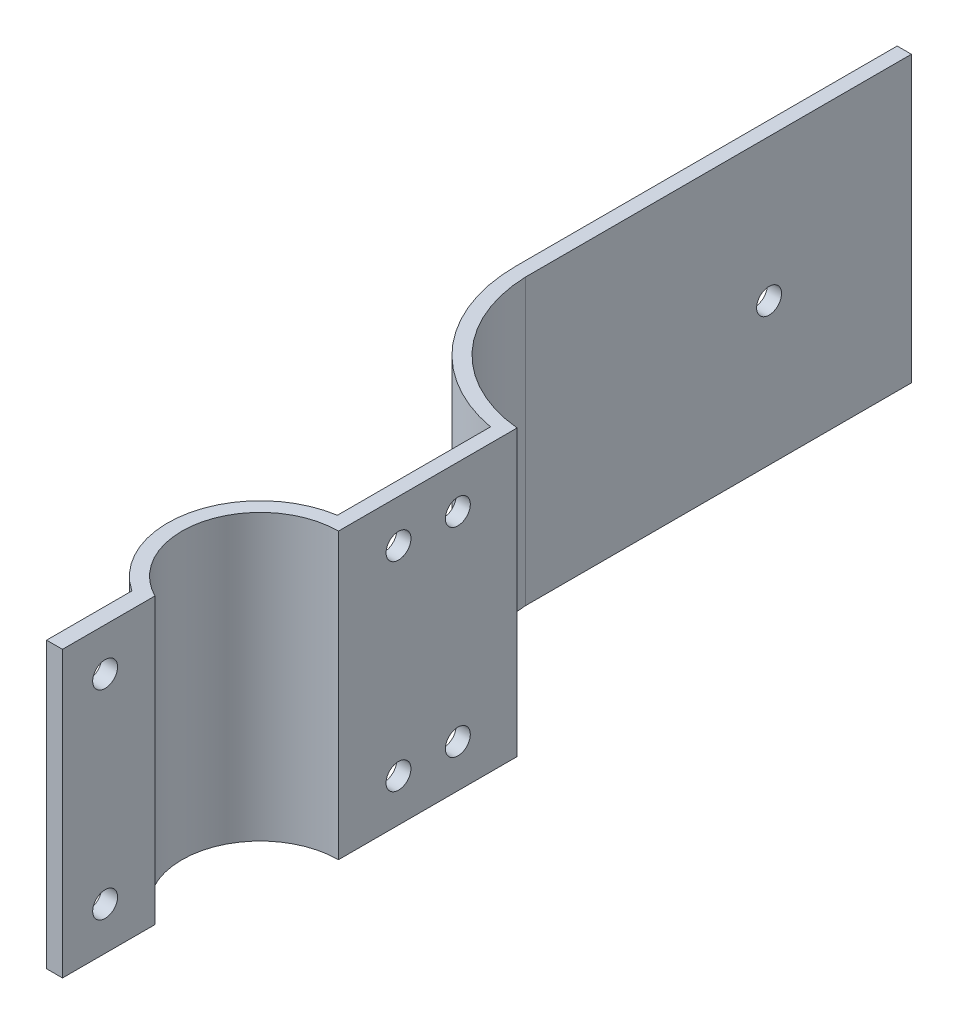
SolidWorks part; units mm, degrees
ref_plane "Front Plane" through (0, 0, 0) normal (0, 0, 1) x (1, 0, 0)
ref_plane "Top Plane" through (0, 0, 0) normal (0, 1, 0) x (1, 0, 0)
ref_plane "Right Plane" through (0, 0, 0) normal (1, 0, 0) x (0, 0, -1)
sketch "Sketch1" plane through (0, 0, 0) normal (0, 1, 0) x (1, 0, 0)
  line L0 (0, 91.2362) -> (0, 0) construction
  line L1 (0, 11) -> (0, 36.0988)
  line L2 (-2, 12.8452) -> (-2, 34.3634)
  line L3 (-19.7762, 55.701) -> (-19.7762, 109.2874)
  line L4 (-5, 25.8533) -> (-2, 25.8533) construction
  line L5 (-15, 136.2362) -> (15, 136.2362) construction
  line L6 (-15, 136.2362) -> (-15, 46.2362) construction
  line L7 (-15, 46.2362) -> (15, 46.2362) construction
  line L8 (15, 136.2362) -> (15, 46.2362) construction
  line L9 (-15, 136.2362) -> (15, 46.2362) construction
  line L10 (-15, 46.2362) -> (15, 136.2362) construction
  line L11 (-5, 15.3533) -> (-2, 15.3533) construction
  line L12 (-5, 15.3533) -> (-5, 20.8533) construction
  line L13 (-5, 20.8533) -> (-2, 20.8533) construction
  line L14 (-2, 15.3533) -> (-2, 20.8533) construction
  line L15 (-5, 15.3533) -> (-2, 20.8533) construction
  line L16 (-5, 20.8533) -> (-2, 15.3533) construction
  line L17 (-5, 25.8533) -> (-5, 31.3533) construction
  line L18 (-5, 31.3533) -> (-2, 31.3533) construction
  line L19 (-2, 25.8533) -> (-2, 31.3533) construction
  line L20 (-5, 25.8533) -> (-2, 31.3533) construction
  line L21 (-5, 31.3533) -> (-2, 25.8533) construction
  line L22 (-5, -9.798) -> (-5, -22.784)
  line L23 (-10.234, -19.9216) -> (-7.234, -19.9216) construction
  line L24 (-10.234, -19.9216) -> (-10.234, -14.4216) construction
  line L25 (-10.234, -14.4216) -> (-7.234, -14.4216) construction
  line L26 (-7.234, -19.9216) -> (-7.234, -14.4216) construction
  line L27 (-10.234, -19.9216) -> (-7.234, -14.4216) construction
  line L28 (-10.234, -14.4216) -> (-7.234, -19.9216) construction
  line L29 (-5, -22.784) -> (-7.234, -22.784)
  line L30 (-7.234, -22.784) -> (-7.234, -10.8013)
  line L31 (-17.7762, 109.2874) -> (-17.7762, 55.0391)
  line L32 (-19.7762, 109.2874) -> (-17.7762, 109.2874)
  line L33 (0, 91.2362) -> (-30.4033, 91.2362) construction
  arc A0 (0, 11) -> (-5, -9.798) centre (0, 0) ccw
  arc A1 (-2, 34.3634) -> (-19.7762, 55.701) centre (1.9182, 55.701) cw
  arc A2 (-2, 12.8452) -> (-7.234, -10.8013) centre (0, 0) ccw
  circle A3 centre (0, 0) radius 11 construction
  circle A4 centre (0, 0) radius 13 construction
  arc A5 (0, 36.0988) -> (-17.7762, 55.0391) centre (1.9144, 55.7075) cw
  point P4 (0, 23.5494)
  point P5 (-8.734, -17.1716)
  point P10 (0, 91.2362)
  point P17 (-3.5, 28.6033)
  point P20 (-3.5, 18.1033)
  point P33 (-17.7762, 117.3644)
  point P43 (-10.0392, -19.1294)
  point P44 (-8.734, -17.1716)
  point P45 (0, 91.2362)
  dimension "D1" = 22
  dimension "D2" = 30
  dimension "D14" = 2
  dimension "D3" = 90
  dimension "D4" = 5.5
  dimension "D5" = 3
  dimension "D6" = 5.5
  dimension "D7" = 3
  dimension "D8" = 2
  dimension "D9" = 5
  dimension "D11" = 5.5
  dimension "D12" = 3
  dimension "D13" = 10
  dimension "D15" = 2
  dimension "D10" = 2
extrude "Boss-Extrude1" add sketch "Sketch1" along normal blind 40
sketch "Sketch3" plane through (-2, 0, 0) normal (-1, 0, 0) x (0, 0, 1)
  line L0 (-109.2874, 20) -> (22.784, 20) construction
  line L1 (-109.2874, 40) -> (-109.2874, 0) construction
  line L2 (22.784, 40) -> (22.784, 0) construction
  line L3 (-17.6846, 6) -> (-12.8452, 6) construction
  line L4 (-34.3634, 40) -> (-12.8452, 40) construction
  line L5 (16.7926, 40) -> (16.7926, 0) construction
  line L6 (10.8013, 40) -> (22.784, 40) construction
  line L7 (10.8013, 0) -> (22.784, 0) construction
  line L8 (-29.524, 34) -> (-34.3634, 34) construction
  line L10 (-34.3634, 40) -> (-34.3634, 0) construction
  line L11 (-26.024, 34) -> (-21.1846, 34) construction
  line L13 (-26.024, 6) -> (-21.1846, 6) construction
  line L14 (-29.524, 6) -> (-34.3634, 6) construction
  line L15 (-17.6846, 34) -> (-12.8452, 34) construction
  line L16 (-12.8452, 40) -> (-12.8452, 0) construction
  circle A0 centre (-27.774, 34) radius 1.75
  circle A1 centre (-19.4346, 34) radius 1.75
  circle A2 centre (16.7926, 34) radius 1.75
  circle A3 centre (-89.2874, 20) radius 1.75
  circle A4 centre (16.7926, 6) radius 1.75
  circle A5 centre (-19.4346, 6) radius 1.75
  circle A6 centre (-27.774, 6) radius 1.75
  point P28 (16.7926, 34)
  point P29 (0, 0)
  point P34 (-92.1249, 20)
  dimension "D1" = 3.5
  dimension "D2" = 6
  dimension "D3" = 20
extrude "Cut-Extrude1" cut sketch "Sketch3" against normal through all both and the other way through all
surface "Surface-Flatten1"
sketch "Sketch4" plane through (-17.7762, 0, -84.5383) normal (1, 0, 0) x (0, 0, -1)
  spline S0 degree 1 poles (-29.4994, 40.0006) (-29.4996, -0.0002) knots 0 0 1 1
  spline S1 degree 1 poles (-57.8475, 40.0008) (-57.8477, -0.0002) knots 0 0 1 1
  spline S2 degree 1 poles (-82.9475, 40.001) (-82.9477, -0.0001) knots 0 0 1 1
  spline S3 degree 1 poles (-112.2678, 40.0012) (-112.2679, 0) knots 0 0 1 1
sketch "Sketch5" plane through (-17.7762, 0, 0) normal (1, 0, 0) x (0, 0, -1)
  line L1 (109.2874, 0) -> (109.2875, 40)
  line L2 (109.2874, 0) -> (109.2875, 40)
  line L3 (-27.7296, 40.0012) -> (1.5907, 40.0012)
  line L4 (-27.7296, 40.0012) -> (-27.7296, 65.0012)
  line L5 (-27.7296, 65.0012) -> (1.5907, 65.0012)
  line L6 (1.5907, 40.0012) -> (1.5907, 65.0012)
  parabola Q1 (-40.7159, -0.0006) -> (-27.7297, 0) focus (-138.4538, -0.1092) apex (-138.4539, -0.1092)
  parabola Q2 (-40.7159, -0.0006) -> (-27.7297, 0) focus (-138.4538, -0.1092) apex (-138.4539, -0.1092)
  spline S0 degree 3 poles (90.4826, 18.7119) (90.7137, 18.9638) (90.8819, 19.2614) (90.9869, 19.5882) (91.0301, 19.9308) (91.0116, 20.276) (90.9314, 20.6107) (90.8122, 20.8704) (90.6856, 21.0577) (90.5385, 21.2298) (90.3205, 21.4151) (90.0201, 21.5839) (89.6932, 21.6966) (89.3522, 21.7491) (89.0096, 21.7369) (88.6781, 21.654) (88.3734, 21.4987) (88.1039, 21.2854) (87.8767, 21.0251) (87.6993, 20.7285) (87.5797, 20.4063) (87.5262, 20.0685) (87.5498, 19.7276) (87.6441, 19.398) (87.7993, 19.0899) (88.0075, 18.8138) (88.2609, 18.5804) (88.5045, 18.4302) (88.7136, 18.3435) (88.9309, 18.281) (89.2147, 18.2478) (89.5578, 18.275) (89.8918, 18.3641) (90.2043, 18.511) (90.4826, 18.7119) (90.7137, 18.9638) (90.8819, 19.2614) knots -0.093675 -0.062171 -0.030937 0 0.030936 0.062171 0.093675 0.125231 0.156591 0.187632 0.203091 0.218563 0.249666 0.281081 0.312648 0.344112 0.37528 0.406182 0.437166 0.468465 0.5 0.531535 0.562834 0.593818 0.62472 0.655889 0.687352 0.718919 0.750335 0.781437 0.796909 0.812368 0.843409 0.874769 0.906325 0.937829 0.969063 1 1.030936 1.062171 1.093675 only from (90.7032, 18.9714) to (90.7032, 18.9714) construction
  spline S1 degree 1 poles (55.0483, 2039.9864) (55.0292, -1999.9856) knots -49.998708 -49.998708 50.998697 50.998697 only from (55.0389, 40.0006) to (55.0387, -0.0002) construction
  spline S2 degree 1 poles (26.7009, 2039.9868) (26.6804, -1999.986) knots -49.99835 -49.99835 50.998346 50.998346 only from (26.6908, 40.0008) to (26.6906, -0.0002) construction
  spline S3 degree 3 poles (17.1703, 7.2881) (16.9392, 7.0362) (16.771, 6.7386) (16.6659, 6.4118) (16.6228, 6.0692) (16.6413, 5.7239) (16.7214, 5.3893) (16.8407, 5.1296) (16.9673, 4.9422) (17.1144, 4.7701) (17.3324, 4.5849) (17.6328, 4.416) (17.9597, 4.3033) (18.3007, 4.2509) (18.6433, 4.2631) (18.9748, 4.346) (19.2796, 4.5013) (19.5491, 4.7146) (19.7763, 4.9749) (19.9537, 5.2715) (20.0733, 5.5937) (20.1268, 5.9315) (20.1032, 6.2724) (20.0089, 6.6021) (19.8537, 6.9101) (19.6454, 7.1862) (19.3921, 7.4197) (19.1485, 7.5698) (18.9394, 7.6565) (18.722, 7.719) (18.4382, 7.7522) (18.0951, 7.725) (17.7611, 7.6359) (17.4486, 7.489) (17.1703, 7.2881) (16.9392, 7.0362) (16.771, 6.7386) knots -0.093676 -0.062172 -0.030937 0 0.030937 0.062172 0.093676 0.125232 0.156592 0.187632 0.203091 0.218563 0.249665 0.28108 0.312647 0.344111 0.37528 0.406182 0.437166 0.468466 0.500001 0.531536 0.562835 0.593818 0.62472 0.655888 0.687352 0.718919 0.750334 0.781437 0.796909 0.812368 0.843409 0.874768 0.906324 0.937828 0.969063 1 1.030937 1.062172 1.093676 only from (16.9497, 7.0286) to (16.9497, 7.0286) construction
  spline S4 degree 3 poles (8.8307, 7.2881) (8.5997, 7.0361) (8.4314, 6.7385) (8.3264, 6.4117) (8.2832, 6.0691) (8.3017, 5.7239) (8.3818, 5.3892) (8.501, 5.1295) (8.6276, 4.9421) (8.7747, 4.7701) (8.9928, 4.5848) (9.2931, 4.416) (9.6201, 4.3033) (9.961, 4.2509) (10.3037, 4.2631) (10.6352, 4.346) (10.94, 4.5013) (11.2095, 4.7146) (11.4367, 4.9749) (11.6141, 5.2715) (11.7337, 5.5937) (11.7872, 5.9315) (11.7637, 6.2724) (11.6694, 6.602) (11.5141, 6.9101) (11.3059, 7.1862) (11.0525, 7.4197) (10.8089, 7.5698) (10.5998, 7.6565) (10.3825, 7.719) (10.0987, 7.7522) (9.7556, 7.725) (9.4216, 7.6359) (9.1091, 7.489) (8.8307, 7.2881) (8.5997, 7.0361) (8.4314, 6.7385) knots -0.093678 -0.062173 -0.030938 0 0.030938 0.062174 0.093679 0.125234 0.156593 0.187632 0.203091 0.218562 0.249663 0.281078 0.312644 0.344109 0.375279 0.406182 0.437167 0.468467 0.500002 0.531537 0.562835 0.593818 0.62472 0.655888 0.687352 0.718919 0.750334 0.781437 0.796908 0.812368 0.843407 0.874766 0.906322 0.937827 0.969062 1 1.030938 1.062174 1.093679 only from (8.6101, 7.0285) to (8.6101, 7.0285) construction
  spline S5 degree 3 poles (19.5608, 32.7126) (19.7918, 32.9645) (19.9601, 33.2621) (20.0651, 33.5889) (20.1083, 33.9315) (20.0898, 34.2767) (20.0096, 34.6114) (19.8904, 34.8711) (19.7638, 35.0585) (19.6167, 35.2305) (19.3987, 35.4158) (19.0983, 35.5846) (18.7714, 35.6974) (18.4304, 35.7498) (18.0878, 35.7377) (17.7563, 35.6547) (17.4515, 35.4995) (17.182, 35.2862) (16.9548, 35.0258) (16.7774, 34.7293) (16.6578, 34.4071) (16.6043, 34.0693) (16.6278, 33.7284) (16.7221, 33.3987) (16.8774, 33.0906) (17.0856, 32.8145) (17.339, 32.5811) (17.5826, 32.4309) (17.7917, 32.3442) (18.009, 32.2817) (18.2929, 32.2485) (18.6359, 32.2757) (18.97, 32.3648) (19.2825, 32.5117) (19.5608, 32.7126) (19.7918, 32.9645) (19.9601, 33.2621) knots -0.093675 -0.062171 -0.030936 0 0.030936 0.062171 0.093675 0.125231 0.156591 0.187631 0.203091 0.218563 0.249665 0.281081 0.312648 0.344112 0.37528 0.406182 0.437166 0.468466 0.500001 0.531536 0.562835 0.593818 0.62472 0.655888 0.687352 0.718919 0.750334 0.781437 0.796909 0.812369 0.843409 0.874769 0.906325 0.937829 0.969064 1 1.030936 1.062171 1.093675 only from (19.7814, 32.9721) to (19.7814, 32.9721) construction
  spline S6 degree 1 poles (1.6008, 2039.9876) (1.5805, -1999.9865) knots -49.998333 -49.998333 50.998329 50.998329 only from (1.5907, 40.001) to (1.5905, -0.0001) construction
  spline S7 degree 3 poles (11.2213, 32.7127) (11.4523, 32.9646) (11.6206, 33.2622) (11.7256, 33.589) (11.7687, 33.9316) (11.7502, 34.2768) (11.67, 34.6115) (11.5507, 34.8712) (11.4241, 35.0586) (11.2771, 35.2306) (11.059, 35.4159) (10.7586, 35.5848) (10.4317, 35.6975) (10.0907, 35.7499) (9.7481, 35.7378) (9.4166, 35.6548) (9.1118, 35.4996) (8.8423, 35.2863) (8.6151, 35.0259) (8.4377, 34.7294) (8.3181, 34.4072) (8.2647, 34.0694) (8.2882, 33.7285) (8.3825, 33.3988) (8.5378, 33.0908) (8.746, 32.8147) (8.9994, 32.5812) (9.243, 32.431) (9.4521, 32.3444) (9.6695, 32.2819) (9.9533, 32.2487) (10.2964, 32.2758) (10.6305, 32.3649) (10.943, 32.5118) (11.2213, 32.7127) (11.4523, 32.9646) (11.6206, 33.2622) knots -0.093672 -0.062169 -0.030935 0 0.030935 0.062169 0.093672 0.125229 0.15659 0.187631 0.203091 0.218563 0.249667 0.281083 0.312649 0.344113 0.375281 0.406182 0.437166 0.468465 0.5 0.531535 0.562835 0.593818 0.624719 0.655887 0.68735 0.718917 0.750333 0.781437 0.796909 0.812369 0.843411 0.874772 0.906328 0.937831 0.969065 1 1.030935 1.062169 1.093672 only from (11.4419, 32.9722) to (11.4419, 32.9722) construction
  spline S8 degree 1 poles (-27.7255, 2039.9874) (-27.7337, -1999.9862) knots -49.998146 -49.998146 50.998146 50.998146 only from (-27.7296, 40.0012) to (-27.7297, 0) construction
  spline S9 degree 3 poles (-33.5297, 4.7116) (-33.2987, 4.9636) (-33.1305, 5.2612) (-33.0255, 5.588) (-32.9824, 5.9306) (-33.001, 6.2758) (-33.0812, 6.6105) (-33.2005, 6.8702) (-33.3271, 7.0576) (-33.4742, 7.2296) (-33.6923, 7.4149) (-33.9926, 7.5838) (-34.3196, 7.6965) (-34.6605, 7.7489) (-35.0032, 7.7368) (-35.3346, 7.6538) (-35.6394, 7.4985) (-35.9088, 7.2852) (-36.136, 7.0248) (-36.3134, 6.7283) (-36.433, 6.406) (-36.4864, 6.0682) (-36.4628, 5.7273) (-36.3685, 5.3977) (-36.2132, 5.0896) (-36.005, 4.8135) (-35.7516, 4.5801) (-35.508, 4.4299) (-35.2989, 4.3432) (-35.0815, 4.2808) (-34.7977, 4.2476) (-34.4546, 4.2748) (-34.1206, 4.3639) (-33.808, 4.5108) (-33.5297, 4.7116) (-33.2987, 4.9636) (-33.1305, 5.2612) knots -0.093672 -0.062168 -0.030935 0 0.030935 0.062168 0.093671 0.125227 0.156589 0.187631 0.203091 0.218564 0.249669 0.281085 0.312652 0.344115 0.375282 0.406182 0.437165 0.468463 0.499998 0.531534 0.562833 0.593818 0.62472 0.655888 0.687351 0.718918 0.750334 0.781437 0.796909 0.812369 0.843411 0.874772 0.906328 0.937832 0.969065 1 1.030935 1.062168 1.093671 only from (-33.3091, 4.9712) to (-33.3091, 4.9712) construction
  spline S10 degree 2 poles (-2890.6646, 41.7357) (1871.493, 39.9865) (82.1632, 40.0001) (-231.366, 40.0025) (3054.6068, 40.0112) knots -64.539315 -64.539315 -64.539315 0.5 0.5 6.755387 6.755387 6.755387 only from (109.2875, 40) to (55.0389, 40.0006)
  spline S11 degree 2 poles (3054.9667, 38.4966) (94.7848, 39.9942) (53.2671, 40.0011) (52.5877, 40.0012) (51.4953, 40.0011) (49.9584, 40.0009) (47.9518, 40.001) (42.2797, 40.0014) (40.8648, 40.0014) (38.2435, 40.0014) (37.8275, 40.0014) (36.8151, 40.0012) (34.7902, 40.0013) (32.8919, 40.0012) (32.006, 40.0011) (31.186, 40.0011) (30.2343, 40.0012) (29.0832, 40.0014) (28.4625, 40.0013) (-13.0552, 39.9958) (-2973.2411, 38.5721) knots -4.331204 -4.331204 -4.331204 0.0625 0.0625 0.125 0.125 0.25 0.25 0.5 0.5 0.607143 0.607143 0.678571 0.75 0.8125 0.8125 0.875 0.875 0.9375 0.9375 5.331207 5.331207 5.331207 only from (55.0389, 40.0006) to (26.6908, 40.0008)
  spline S12 degree 2 poles (-2973.2494, 40.7154) (186.3714, 39.9979) (22.1728, 40.0007) (20.6668, 40.0008) (19.1608, 40.0008) (16.2785, 40.0008) (14.1408, 40.0009) (8.431, 40.0009) (7.8657, 40.0009) (-136.8171, 40.0017) (3001.5238, 39.9942) knots -10.715936 -10.715936 -10.715936 0.18 0.18 0.3 0.3 0.5 0.5 0.75 0.75 7.240324 7.240324 7.240324 only from (26.6908, 40.0008) to (1.5907, 40.001)
  spline S13 degree 2 poles (3001.503, 41.3779) (41.9721, 39.9891) (-0.2418, 40.001) (-0.8609, 40.0012) (-2.0743, 40.0022) (-3.0746, 40.003) (-3.9068, 40.0033) (-4.254, 40.0034) (-4.8231, 40.0036) (-5.6823, 40.0038) (-5.7393, 40.0038) (-7.5719, 40.0044) (-9.4044, 40.0048) (-11.0719, 40.0052) (-13.0694, 40.0052) (-15.4062, 40.0052) (-16.7345, 40.0048) (-18.567, 40.0043) (-20.3995, 40.0039) (-22.1596, 40.0034) (-22.232, 40.0034) (-23.0638, 40.0031) (-24.0645, 40.0023) (-25.2758, 40.0013) (-25.8971, 40.0012) (-68.1109, 39.9905) (-3027.6324, 41.4754) knots -4.256746 -4.256746 -4.256746 0.0625 0.0625 0.125 0.125 0.1875 0.1875 0.21875 0.21875 0.25 0.25 0.375 0.375 0.5 0.5 0.625 0.625 0.75 0.75 0.8125 0.8125 0.875 0.875 0.9375 0.9375 5.25674 5.25674 5.25674 only from (1.5907, 40.001) to (-27.7296, 40.0012)
  spline S14 degree 2 poles (-3027.6872, 41.3331) (3023.5471, 38.875) (-3040.5904, 40.9535) knots -49.147891 -49.147891 -49.147891 41.446984 41.446984 41.446984 only from (-27.7296, 40.0012) to (-40.7158, 40.0018)
  spline S15 degree 2 poles (-41.0189, -2959.4443) (-40.6984, 213.3169) (-40.7168, 30.0012) (-40.7174, 24.1126) (-40.7174, 20.0006) (-40.7174, 15.0372) (-40.7169, 10) (-40.5512, -1494.9744) (-53.4953, -2999.95) knots -4.494286 -4.494286 -4.494286 0.25 0.25 0.5 0.5 0.75 0.75 75.994152 75.994152 75.994152 only from (-40.7158, 40.0018) to (-40.7159, -0.0006)
  spline S16 degree 2 poles (-3027.6407, -1.6375) (-68.111, 0.0098) (-25.8971, 0) (-25.2009, -0.0001) (-24.0646, -0.0011) (-21.995, -0.0028) (-20.3996, -0.0031) (-18.8289, -0.0034) (-17.2582, -0.0037) (-15.3316, -0.0041) (-13.0696, -0.0041) (-10.6997, -0.0041) (-9.4045, -0.0038) (-7.572, -0.0033) (-5.7395, -0.0028) (-4.0471, -0.0024) (-3.907, -0.0023) (-3.0751, -0.002) (-2.0745, -0.0012) (-0.8612, -0.0003) (-0.242, -0.0001) (41.9718, 0.0112) (3001.49, -1.4164) knots -4.256754 -4.256754 -4.256754 0.0625 0.0625 0.125 0.125 0.25 0.25 0.357143 0.357143 0.5 0.5 0.625 0.625 0.75 0.75 0.8125 0.8125 0.875 0.875 0.9375 0.9375 5.256746 5.256746 5.256746 only from (-27.7297, 0) to (1.5905, -0.0001)
  spline S17 degree 2 poles (-2998.3919, 2.4591) (-1492.1257, -0.0033) (14.1406, -0.0001) (15.3297, -0.0001) (19.5191, -0.0001) (21.5169, -0.0001) (23.1048, 0) (131.3492, 0.0017) (3026.0442, -1.0974) knots -119.521164 -119.521164 -119.521164 0.5 0.5 0.714286 0.714286 0.857143 0.857143 11.039672 11.039672 11.039672 only from (1.5905, -0.0001) to (26.6906, -0.0002)
  spline S18 degree 2 poles (-2973.2389, 1.461) (-13.0554, 0.0052) (28.4623, -0.0007) (29.0791, -0.0008) (30.2341, -0.0006) (31.3259, -0.0005) (32.0058, -0.0006) (32.8917, -0.0007) (33.7776, -0.0007) (39.1537, -0.0009) (40.8646, -0.0009) (42.4317, -0.0008) (47.9516, -0.0006) (49.9729, -0.0005) (51.4952, -0.0006) (52.588, -0.0008) (53.2669, -0.0007) (94.7847, 0.0058) (3054.972, 1.4799) knots -4.331204 -4.331204 -4.331204 0.0625 0.0625 0.125 0.125 0.1875 0.1875 0.25 0.25 0.5 0.5 0.75 0.75 0.875 0.875 0.9375 0.9375 5.331207 5.331207 5.331207 only from (26.6906, -0.0002) to (55.0387, -0.0002)
  spline S19 degree 2 poles (3054.9167, -0.0382) (-2972.3309, 0.0322) (3109.2583, -0.0271) knots -7.994831 -7.994831 -7.994831 7.930127 7.930127 7.930127 only from (55.0387, -0.0002) to (109.2874, 0)
  spline S20 degree 2 poles (109.2875, 40) (95.9189, 40) (82.1632, 40.0001) (57.1024, 40.0003) (55.0389, 40.0006) knots 0 0 0 0.5 0.5 1 1 1
  spline S21 degree 2 poles (55.0389, 40.0006) (53.8577, 40.001) (53.2671, 40.0011) (52.5877, 40.0012) (51.4953, 40.0011) (49.9584, 40.0009) (47.9518, 40.001) (42.2797, 40.0014) (40.8648, 40.0014) (38.2435, 40.0014) (37.8275, 40.0014) (36.8151, 40.0012) (34.7902, 40.0013) (32.8919, 40.0012) (32.006, 40.0011) (31.186, 40.0011) (30.2343, 40.0012) (29.0832, 40.0014) (28.4625, 40.0013) (27.8719, 40.0012) (26.6908, 40.0008) knots 0 0 0 0.0625 0.0625 0.125 0.125 0.25 0.25 0.5 0.5 0.607143 0.607143 0.678571 0.75 0.8125 0.8125 0.875 0.875 0.9375 0.9375 1 1 1
  spline S22 degree 2 poles (26.6908, 40.0008) (24.8853, 40.0007) (22.1728, 40.0007) (20.6668, 40.0008) (19.1608, 40.0008) (16.2785, 40.0008) (14.1408, 40.0009) (8.431, 40.0009) (7.8657, 40.0009) (2.2927, 40.001) (1.5907, 40.001) knots 0 0 0 0.18 0.18 0.3 0.3 0.5 0.5 0.75 0.75 1 1 1
  spline S23 degree 2 poles (1.5907, 40.001) (0.3691, 40.0009) (-0.2418, 40.001) (-0.8609, 40.0012) (-2.0743, 40.0022) (-3.0746, 40.003) (-3.9068, 40.0033) (-4.254, 40.0034) (-4.8231, 40.0036) (-5.6823, 40.0038) (-5.7393, 40.0038) (-7.5719, 40.0044) (-9.4044, 40.0048) (-11.0719, 40.0052) (-13.0694, 40.0052) (-15.4062, 40.0052) (-16.7345, 40.0048) (-18.567, 40.0043) (-20.3995, 40.0039) (-22.1596, 40.0034) (-22.232, 40.0034) (-23.0638, 40.0031) (-24.0645, 40.0023) (-25.2758, 40.0013) (-25.8971, 40.0012) (-26.5079, 40.001) (-27.7296, 40.0012) knots 0 0 0 0.0625 0.0625 0.125 0.125 0.1875 0.1875 0.21875 0.21875 0.25 0.25 0.375 0.375 0.5 0.5 0.625 0.625 0.75 0.75 0.8125 0.8125 0.875 0.875 0.9375 0.9375 1 1 1
  spline S24 degree 2 poles (-27.7296, 40.0012) (-33.4846, 40.0012) (-40.7158, 40.0018) knots 0 0 0 1 1 1
  spline S25 degree 2 poles (-40.7158, 40.0018) (-40.7158, 39.661) (-40.7168, 30.0012) (-40.7174, 24.1126) (-40.7174, 20.0006) (-40.7174, 15.0372) (-40.7169, 10) (-40.7163, 4.9997) (-40.7159, -0.0006) knots 0 0 0 0.25 0.25 0.5 0.5 0.75 0.75 1 1 1
  spline S26 degree 2 poles (-27.7297, 0) (-26.508, 0.0002) (-25.8971, 0) (-25.2009, -0.0001) (-24.0646, -0.0011) (-21.995, -0.0028) (-20.3996, -0.0031) (-18.8289, -0.0034) (-17.2582, -0.0037) (-15.3316, -0.0041) (-13.0696, -0.0041) (-10.6997, -0.0041) (-9.4045, -0.0038) (-7.572, -0.0033) (-5.7395, -0.0028) (-4.0471, -0.0024) (-3.907, -0.0023) (-3.0751, -0.002) (-2.0745, -0.0012) (-0.8612, -0.0003) (-0.242, -0.0001) (0.3689, 0.0001) (1.5905, -0.0001) knots 0 0 0 0.0625 0.0625 0.125 0.125 0.25 0.25 0.357143 0.357143 0.5 0.5 0.625 0.625 0.75 0.75 0.8125 0.8125 0.875 0.875 0.9375 0.9375 1 1 1
  spline S27 degree 2 poles (1.5905, -0.0001) (7.8655, -0.0001) (14.1406, -0.0001) (15.3297, -0.0001) (19.5191, -0.0001) (21.5169, -0.0001) (23.1048, 0) (24.6235, 0) (26.6906, -0.0002) knots 0 0 0 0.5 0.5 0.714286 0.714286 0.857143 0.857143 1 1 1
  spline S28 degree 2 poles (26.6906, -0.0002) (27.8717, -0.0006) (28.4623, -0.0007) (29.0791, -0.0008) (30.2341, -0.0006) (31.3259, -0.0005) (32.0058, -0.0006) (32.8917, -0.0007) (33.7776, -0.0007) (39.1537, -0.0009) (40.8646, -0.0009) (42.4317, -0.0008) (47.9516, -0.0006) (49.9729, -0.0005) (51.4952, -0.0006) (52.588, -0.0008) (53.2669, -0.0007) (53.8575, -0.0006) (55.0387, -0.0002) knots 0 0 0 0.0625 0.0625 0.125 0.125 0.1875 0.1875 0.25 0.25 0.5 0.5 0.75 0.75 0.875 0.875 0.9375 0.9375 1 1 1
  spline S29 degree 2 poles (55.0387, -0.0002) (58.2895, 0.0001) (109.2874, 0) knots 0 0 0 1 1 1
  spline S30 degree 3 poles (-33.53, 32.7132) (-33.2989, 32.9651) (-33.1306, 33.2627) (-33.0255, 33.5895) (-32.9824, 33.9321) (-33.0008, 34.2773) (-33.0809, 34.612) (-33.2001, 34.8717) (-33.3267, 35.0591) (-33.4737, 35.2311) (-33.6918, 35.4164) (-33.9922, 35.5852) (-34.3191, 35.698) (-34.6601, 35.7504) (-35.0027, 35.7382) (-35.3342, 35.6553) (-35.639, 35.5001) (-35.9085, 35.2868) (-36.1357, 35.0264) (-36.3132, 34.7299) (-36.4328, 34.4077) (-36.4863, 34.0699) (-36.4628, 33.729) (-36.3685, 33.3993) (-36.2133, 33.0912) (-36.0051, 32.8151) (-35.7517, 32.5816) (-35.5082, 32.4314) (-35.2991, 32.3447) (-35.0818, 32.2822) (-34.7979, 32.2491) (-34.4549, 32.2762) (-34.1208, 32.3654) (-33.8083, 32.5122) (-33.53, 32.7132) (-33.2989, 32.9651) (-33.1306, 33.2627) knots -0.093679 -0.062175 -0.030938 0 0.030939 0.062175 0.093679 0.125235 0.156594 0.187632 0.203091 0.218562 0.249663 0.281078 0.312645 0.344109 0.375279 0.406182 0.437166 0.468466 0.500001 0.531536 0.562835 0.593818 0.62472 0.655889 0.687354 0.71892 0.750335 0.781437 0.796908 0.812367 0.843406 0.874765 0.906321 0.937825 0.969062 1 1.030939 1.062175 1.093679 only from (-33.3093, 32.9727) to (-33.3093, 32.9727) construction
  spline S31 degree 3 poles (90.4826, 18.7119) (90.7137, 18.9638) (90.8819, 19.2614) (90.9869, 19.5882) (91.0301, 19.9308) (91.0116, 20.276) (90.9314, 20.6107) (90.8122, 20.8704) (90.6856, 21.0577) (90.5385, 21.2298) (90.3205, 21.4151) (90.0201, 21.5839) (89.6932, 21.6966) (89.3522, 21.7491) (89.0096, 21.7369) (88.6781, 21.654) (88.3734, 21.4987) (88.1039, 21.2854) (87.8767, 21.0251) (87.6993, 20.7285) (87.5797, 20.4063) (87.5262, 20.0685) (87.5498, 19.7276) (87.6441, 19.398) (87.7993, 19.0899) (88.0075, 18.8138) (88.2609, 18.5804) (88.5045, 18.4302) (88.7136, 18.3435) (88.9309, 18.281) (89.2147, 18.2478) (89.5578, 18.275) (89.8918, 18.3641) (90.2043, 18.511) (90.4826, 18.7119) (90.7137, 18.9638) (90.8819, 19.2614) knots -0.093675 -0.062171 -0.030937 0 0.030936 0.062171 0.093675 0.125231 0.156591 0.187632 0.203091 0.218563 0.249666 0.281081 0.312648 0.344112 0.37528 0.406182 0.437166 0.468465 0.5 0.531535 0.562834 0.593818 0.62472 0.655889 0.687352 0.718919 0.750335 0.781437 0.796909 0.812368 0.843409 0.874769 0.906325 0.937829 0.969063 1 1.030936 1.062171 1.093675 only from (90.7032, 18.9714) to (90.7032, 18.9714)
  spline S32 degree 1 poles (55.0389, 40.0006) (55.0387, -0.0002) knots 0 0 1 1
  spline S33 degree 1 poles (26.6908, 40.0008) (26.6906, -0.0002) knots 0 0 1 1
  spline S34 degree 3 poles (17.1703, 7.2881) (16.9392, 7.0362) (16.771, 6.7386) (16.6659, 6.4118) (16.6228, 6.0692) (16.6413, 5.7239) (16.7214, 5.3893) (16.8407, 5.1296) (16.9673, 4.9422) (17.1144, 4.7701) (17.3324, 4.5849) (17.6328, 4.416) (17.9597, 4.3033) (18.3007, 4.2509) (18.6433, 4.2631) (18.9748, 4.346) (19.2796, 4.5013) (19.5491, 4.7146) (19.7763, 4.9749) (19.9537, 5.2715) (20.0733, 5.5937) (20.1268, 5.9315) (20.1032, 6.2724) (20.0089, 6.6021) (19.8537, 6.9101) (19.6454, 7.1862) (19.3921, 7.4197) (19.1485, 7.5698) (18.9394, 7.6565) (18.722, 7.719) (18.4382, 7.7522) (18.0951, 7.725) (17.7611, 7.6359) (17.4486, 7.489) (17.1703, 7.2881) (16.9392, 7.0362) (16.771, 6.7386) knots -0.093676 -0.062172 -0.030937 0 0.030937 0.062172 0.093676 0.125232 0.156592 0.187632 0.203091 0.218563 0.249665 0.28108 0.312647 0.344111 0.37528 0.406182 0.437166 0.468466 0.500001 0.531536 0.562835 0.593818 0.62472 0.655888 0.687352 0.718919 0.750334 0.781437 0.796909 0.812368 0.843409 0.874768 0.906324 0.937828 0.969063 1 1.030937 1.062172 1.093676 only from (16.9497, 7.0286) to (16.9497, 7.0286)
  spline S35 degree 3 poles (8.8307, 7.2881) (8.5997, 7.0361) (8.4314, 6.7385) (8.3264, 6.4117) (8.2832, 6.0691) (8.3017, 5.7239) (8.3818, 5.3892) (8.501, 5.1295) (8.6276, 4.9421) (8.7747, 4.7701) (8.9928, 4.5848) (9.2931, 4.416) (9.6201, 4.3033) (9.961, 4.2509) (10.3037, 4.2631) (10.6352, 4.346) (10.94, 4.5013) (11.2095, 4.7146) (11.4367, 4.9749) (11.6141, 5.2715) (11.7337, 5.5937) (11.7872, 5.9315) (11.7637, 6.2724) (11.6694, 6.602) (11.5141, 6.9101) (11.3059, 7.1862) (11.0525, 7.4197) (10.8089, 7.5698) (10.5998, 7.6565) (10.3825, 7.719) (10.0987, 7.7522) (9.7556, 7.725) (9.4216, 7.6359) (9.1091, 7.489) (8.8307, 7.2881) (8.5997, 7.0361) (8.4314, 6.7385) knots -0.093678 -0.062173 -0.030938 0 0.030938 0.062174 0.093679 0.125234 0.156593 0.187632 0.203091 0.218562 0.249663 0.281078 0.312644 0.344109 0.375279 0.406182 0.437167 0.468467 0.500002 0.531537 0.562835 0.593818 0.62472 0.655888 0.687352 0.718919 0.750334 0.781437 0.796908 0.812368 0.843407 0.874766 0.906322 0.937827 0.969062 1 1.030938 1.062174 1.093679 only from (8.6101, 7.0285) to (8.6101, 7.0285)
  spline S36 degree 3 poles (19.5608, 32.7126) (19.7918, 32.9645) (19.9601, 33.2621) (20.0651, 33.5889) (20.1083, 33.9315) (20.0898, 34.2767) (20.0096, 34.6114) (19.8904, 34.8711) (19.7638, 35.0585) (19.6167, 35.2305) (19.3987, 35.4158) (19.0983, 35.5846) (18.7714, 35.6974) (18.4304, 35.7498) (18.0878, 35.7377) (17.7563, 35.6547) (17.4515, 35.4995) (17.182, 35.2862) (16.9548, 35.0258) (16.7774, 34.7293) (16.6578, 34.4071) (16.6043, 34.0693) (16.6278, 33.7284) (16.7221, 33.3987) (16.8774, 33.0906) (17.0856, 32.8145) (17.339, 32.5811) (17.5826, 32.4309) (17.7917, 32.3442) (18.009, 32.2817) (18.2929, 32.2485) (18.6359, 32.2757) (18.97, 32.3648) (19.2825, 32.5117) (19.5608, 32.7126) (19.7918, 32.9645) (19.9601, 33.2621) knots -0.093675 -0.062171 -0.030936 0 0.030936 0.062171 0.093675 0.125231 0.156591 0.187631 0.203091 0.218563 0.249665 0.281081 0.312648 0.344112 0.37528 0.406182 0.437166 0.468466 0.500001 0.531536 0.562835 0.593818 0.62472 0.655888 0.687352 0.718919 0.750334 0.781437 0.796909 0.812369 0.843409 0.874769 0.906325 0.937829 0.969064 1 1.030936 1.062171 1.093675 only from (19.7814, 32.9721) to (19.7814, 32.9721)
  spline S37 degree 1 poles (1.5907, 40.001) (1.5905, -0.0001) knots 0 0 1 1
  spline S38 degree 3 poles (11.2213, 32.7127) (11.4523, 32.9646) (11.6206, 33.2622) (11.7256, 33.589) (11.7687, 33.9316) (11.7502, 34.2768) (11.67, 34.6115) (11.5507, 34.8712) (11.4241, 35.0586) (11.2771, 35.2306) (11.059, 35.4159) (10.7586, 35.5848) (10.4317, 35.6975) (10.0907, 35.7499) (9.7481, 35.7378) (9.4166, 35.6548) (9.1118, 35.4996) (8.8423, 35.2863) (8.6151, 35.0259) (8.4377, 34.7294) (8.3181, 34.4072) (8.2647, 34.0694) (8.2882, 33.7285) (8.3825, 33.3988) (8.5378, 33.0908) (8.746, 32.8147) (8.9994, 32.5812) (9.243, 32.431) (9.4521, 32.3444) (9.6695, 32.2819) (9.9533, 32.2487) (10.2964, 32.2758) (10.6305, 32.3649) (10.943, 32.5118) (11.2213, 32.7127) (11.4523, 32.9646) (11.6206, 33.2622) knots -0.093672 -0.062169 -0.030935 0 0.030935 0.062169 0.093672 0.125229 0.15659 0.187631 0.203091 0.218563 0.249667 0.281083 0.312649 0.344113 0.375281 0.406182 0.437166 0.468465 0.5 0.531535 0.562835 0.593818 0.624719 0.655887 0.68735 0.718917 0.750333 0.781437 0.796909 0.812369 0.843411 0.874772 0.906328 0.937831 0.969065 1 1.030935 1.062169 1.093672 only from (11.4419, 32.9722) to (11.4419, 32.9722)
  spline S39 degree 1 poles (-27.7296, 40.0012) (-27.7297, 0) knots 0 0 1 1
  spline S40 degree 3 poles (-33.5297, 4.7116) (-33.2987, 4.9636) (-33.1305, 5.2612) (-33.0255, 5.588) (-32.9824, 5.9306) (-33.001, 6.2758) (-33.0812, 6.6105) (-33.2005, 6.8702) (-33.3271, 7.0576) (-33.4742, 7.2296) (-33.6923, 7.4149) (-33.9926, 7.5838) (-34.3196, 7.6965) (-34.6605, 7.7489) (-35.0032, 7.7368) (-35.3346, 7.6538) (-35.6394, 7.4985) (-35.9088, 7.2852) (-36.136, 7.0248) (-36.3134, 6.7283) (-36.433, 6.406) (-36.4864, 6.0682) (-36.4628, 5.7273) (-36.3685, 5.3977) (-36.2132, 5.0896) (-36.005, 4.8135) (-35.7516, 4.5801) (-35.508, 4.4299) (-35.2989, 4.3432) (-35.0815, 4.2808) (-34.7977, 4.2476) (-34.4546, 4.2748) (-34.1206, 4.3639) (-33.808, 4.5108) (-33.5297, 4.7116) (-33.2987, 4.9636) (-33.1305, 5.2612) knots -0.093672 -0.062168 -0.030935 0 0.030935 0.062168 0.093671 0.125227 0.156589 0.187631 0.203091 0.218564 0.249669 0.281085 0.312652 0.344115 0.375282 0.406182 0.437165 0.468463 0.499998 0.531534 0.562833 0.593818 0.62472 0.655888 0.687351 0.718918 0.750334 0.781437 0.796909 0.812369 0.843411 0.874772 0.906328 0.937832 0.969065 1 1.030935 1.062168 1.093671 only from (-33.3091, 4.9712) to (-33.3091, 4.9712)
  spline S41 degree 3 poles (-33.53, 32.7132) (-33.2989, 32.9651) (-33.1306, 33.2627) (-33.0255, 33.5895) (-32.9824, 33.9321) (-33.0008, 34.2773) (-33.0809, 34.612) (-33.2001, 34.8717) (-33.3267, 35.0591) (-33.4737, 35.2311) (-33.6918, 35.4164) (-33.9922, 35.5852) (-34.3191, 35.698) (-34.6601, 35.7504) (-35.0027, 35.7382) (-35.3342, 35.6553) (-35.639, 35.5001) (-35.9085, 35.2868) (-36.1357, 35.0264) (-36.3132, 34.7299) (-36.4328, 34.4077) (-36.4863, 34.0699) (-36.4628, 33.729) (-36.3685, 33.3993) (-36.2133, 33.0912) (-36.0051, 32.8151) (-35.7517, 32.5816) (-35.5082, 32.4314) (-35.2991, 32.3447) (-35.0818, 32.2822) (-34.7979, 32.2491) (-34.4549, 32.2762) (-34.1208, 32.3654) (-33.8083, 32.5122) (-33.53, 32.7132) (-33.2989, 32.9651) (-33.1306, 33.2627) knots -0.093679 -0.062175 -0.030938 0 0.030939 0.062175 0.093679 0.125235 0.156594 0.187632 0.203091 0.218562 0.249663 0.281078 0.312645 0.344109 0.375279 0.406182 0.437166 0.468466 0.500001 0.531536 0.562835 0.593818 0.62472 0.655889 0.687354 0.71892 0.750335 0.781437 0.796908 0.812367 0.843406 0.874765 0.906321 0.937825 0.969062 1 1.030939 1.062175 1.093679 only from (-33.3093, 32.9727) to (-33.3093, 32.9727)
  point P31 (-34.8524, 33.8692)
  point P32 (18.3218, 33.8692)
  point P33 (89.3035, 19.9222)
  point P34 (9.9466, 33.8692)
  dimension "D2" = 12.9862
  dimension "D3" = 29.3203
  dimension "D4" = 25.1
  dimension "D5" = 28.3481
  dimension "D6" = 54.2486
  dimension "D7" = 150.0033
  dimension "D8" = 5.8634
  dimension "D9" = 50.6624
  dimension "D10" = 59.0376
  dimension "D11" = 6.1326
  dimension "D12" = 19.984
  dimension "D13" = 25
  dimension "D14" = 29.3203
  dimension "D1" = 0
